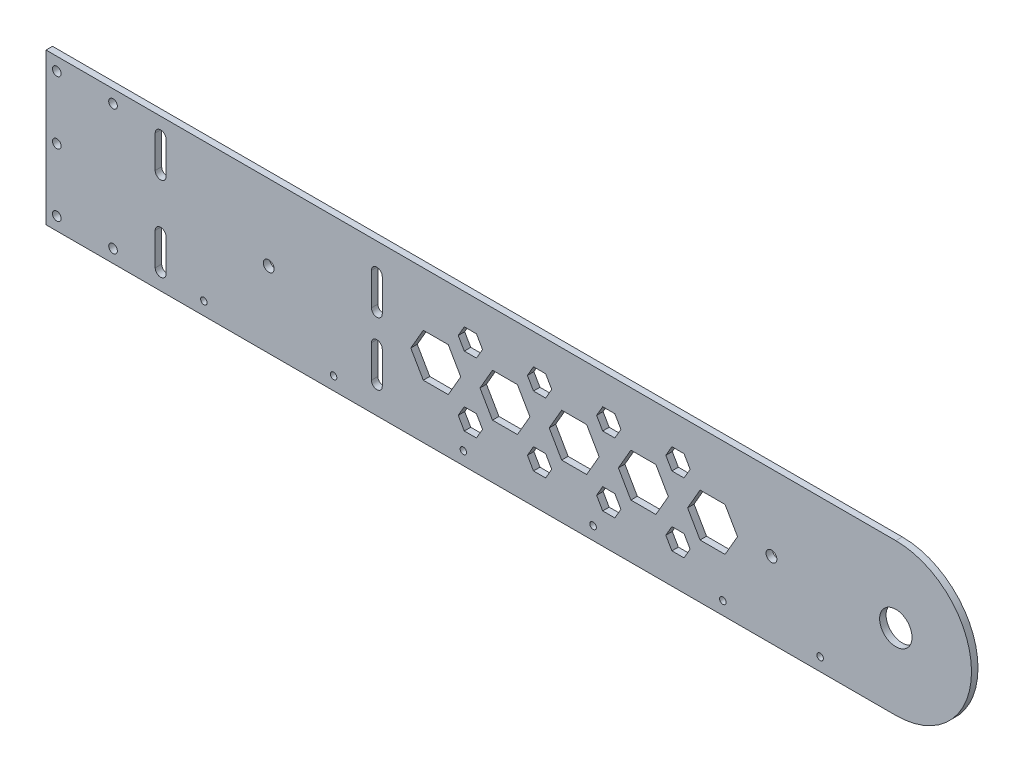
SolidWorks part; units mm, degrees
material "6061 Alloy"
ref_plane "Front Plane" through (0, 0, 0) normal (0, 0, 1) x (1, 0, 0)
ref_plane "Top Plane" through (0, 0, 0) normal (0, 1, 0) x (1, 0, 0)
ref_plane "Right Plane" through (0, 0, 0) normal (1, 0, 0) x (0, 0, -1)
sketch "Sketch1" plane through (0, 0, 0) normal (0, 0, 1) x (1, 0, 0)
  line L0 (0, 0) -> (45.8221, 0) construction
  line L1 (0, 35) -> (393, 35) construction
  line L2 (0, 35) -> (0, -35)
  line L3 (0, -35) -> (393, -35) construction
  line L5 (0, 35) -> (393, 35)
  line L6 (393, -35) -> (0, -35)
  circle A0 centre (5, 29) radius 2
  circle A2 centre (5, -29) radius 2
  circle A4 centre (393, 0) radius 7.5
  circle A7 centre (103, 0) radius 2.5
  circle A8 centre (31, 29) radius 2
  circle A9 centre (31, -29) radius 2
  circle A10 centre (5, 0) radius 2
  arc A11 (393, 35) -> (393, -35) centre (393, 0) cw
  point P0 (0, 0)
  point P8 (153, 0)
  point P14 (53, 0)
  point P16 (0, 0)
  dimension "D2" = 4
  dimension "D5" = 393
  dimension "D10" = 15
  dimension "D6" = 50
  dimension "D7" = 50
  dimension "D14" = 5
  dimension "D8" = 4
  dimension "D11" = 4
  dimension "D15" = 4
  dimension "D1" = 70
  dimension "D3" = 5
  dimension "D4" = 6
  dimension "D9" = 0
  dimension "D12" = 290
  dimension "D13" = 26
extrude "Boss-Extrude1" add sketch "Sketch1" along normal blind 3
sketch "Sketch3" plane through (0, 0, 3) normal (0, 0, 1) x (1, 0, 0)
  line L0 (53, 110.2799) -> (53, -110.2799)
  line L1 (153, 124.2968) -> (153, -124.2968)
  circle A0 centre (103, 0) radius 2.5 construction
  point P3 (53, 0)
  point P6 (153, 0)
  dimension "D1" = 50
  dimension "D2" = 50
split line "Split Line1" [suppressed]
sketch "Sketch4" plane through (0, 0, 3) normal (0, 0, 1) x (1, 0, 0)
  line L0 (53, 27) -> (53, 12) construction
  line L1 (55.5, 27) -> (55.5, 12)
  line L2 (50.5, 27) -> (50.5, 12)
  line L3 (153, 22) -> (153, 7) construction
  line L4 (155.5, 22) -> (155.5, 7)
  line L5 (150.5, 22) -> (150.5, 7)
  line L6 (53, 0) -> (153, 0) construction
  line L7 (153, -22) -> (153, -7) construction
  line L8 (155.5, -22) -> (155.5, -7)
  line L9 (150.5, -22) -> (150.5, -7)
  line L10 (53, -27) -> (53, -12) construction
  line L11 (55.5, -27) -> (55.5, -12)
  line L12 (50.5, -27) -> (50.5, -12)
  arc A0 (55.5, 27) -> (50.5, 27) centre (53, 27) ccw
  arc A1 (50.5, 12) -> (55.5, 12) centre (53, 12) ccw
  arc A2 (155.5, 22) -> (150.5, 22) centre (153, 22) ccw
  arc A3 (150.5, 7) -> (155.5, 7) centre (153, 7) ccw
  circle A4 centre (103, 0) radius 2.5 construction
  arc A5 (155.5, -22) -> (150.5, -22) centre (153, -22) cw
  arc A6 (150.5, -7) -> (155.5, -7) centre (153, -7) cw
  arc A7 (55.5, -27) -> (50.5, -27) centre (53, -27) cw
  arc A8 (50.5, -12) -> (55.5, -12) centre (53, -12) cw
  point P2 (53, 19.5)
  point P8 (153, 14.5)
  point P23 (153, -14.5)
  point P30 (53, -19.5)
  dimension "D1" = 2.5
  dimension "D2" = 2.5
  dimension "D4" = 50
  dimension "D3" = 50
  dimension "D5" = 22
  dimension "D6" = 12
  dimension "D7" = 27
  dimension "D8" = 7
extrude "Cut-Extrude1" cut sketch "Sketch4" against normal through all both and the other way through all
sketch "Sketch5" plane through (0, 0, 3) normal (0, 0, 1) x (1, 0, 0)
  line L0 (284.5811, 0) -> (386.4189, 0) construction
  circle A2 centre (335.5, 0) radius 2.5
  circle A3 centre (103, 0) radius 2.5 construction
  dimension "D1" = 5
  dimension "D2" = 232.5
extrude "Cut-Extrude2" cut sketch "Sketch5" against normal through all both and the other way through all
sketch "Sketch6" plane through (0, 0, 3) normal (0, 0, 1) x (1, 0, 0)
  circle A4 centre (421, 0) radius 1.5
  circle A5 centre (393, -28) radius 1.5
  circle A6 centre (393, 28) radius 1.5
  circle A7 centre (393, 0) radius 7.5 construction
  circle A8 centre (365, 0) radius 1.5
  point P13 (393, 0)
  dimension "D1" = 3
  dimension "D2" = 0
  dimension "D3" = 28
extrude "Cut-Extrude3" [suppressed] cut sketch "Sketch6" against normal through all both and the other way through all
sketch "Sketch7" plane through (0, 0, 3) normal (0, 0, 1) x (1, 0, 0)
  line L1 (73, -29) -> (133, -29) construction
  line L2 (0, -35) -> (393, -35) construction
  circle A0 centre (73, -29) radius 1.5
  circle A2 centre (133, -29) radius 1.5
  circle A3 centre (193, -29) radius 1.5
  circle A4 centre (253, -29) radius 1.5
  circle A5 centre (313, -29) radius 1.5
  circle A12 centre (358, -29) radius 1.5
  circle A13 centre (103, 0) radius 2.5 construction
  dimension "D1" = 3
  dimension "D6" = 3
  dimension "D3" = 30
  dimension "D2" = 6
  dimension "D5" = 60
  dimension "D7" = 45
  dimension "D4" = 5
extrude "Cut-Extrude4" cut sketch "Sketch7" against normal blind 3
sketch "Sketch9" plane through (0, 0, 3) normal (0, 0, 1) x (1, 0, 0)
  line L0 (164.5554, 0) -> (302.378, 0) construction
  line L1 (223.795, 0) -> (218.0215, 10)
  line L2 (191.795, 0) -> (186.0215, 10)
  line L3 (186.0215, 10) -> (174.4745, 10)
  line L4 (174.4745, 10) -> (168.701, 0)
  line L5 (168.701, 0) -> (174.4745, -10)
  line L6 (174.4745, -10) -> (186.0215, -10)
  line L7 (186.0215, -10) -> (191.795, 0)
  line L8 (218.0215, 10) -> (206.4745, 10)
  line L9 (206.4745, 10) -> (200.701, 0)
  line L10 (200.701, 0) -> (206.4745, -10)
  line L11 (206.4745, -10) -> (218.0215, -10)
  line L12 (218.0215, -10) -> (223.795, 0)
  line L13 (255.795, 0) -> (250.0215, 10)
  line L14 (250.0215, 10) -> (238.4745, 10)
  line L15 (238.4745, 10) -> (232.701, 0)
  line L16 (232.701, 0) -> (238.4745, -10)
  line L17 (238.4745, -10) -> (250.0215, -10)
  line L18 (250.0215, -10) -> (255.795, 0)
  line L19 (287.795, 0) -> (282.0215, 10)
  line L20 (282.0215, 10) -> (270.4745, 10)
  line L21 (270.4745, 10) -> (264.701, 0)
  line L22 (264.701, 0) -> (270.4745, -10)
  line L23 (270.4745, -10) -> (282.0215, -10)
  line L24 (282.0215, -10) -> (287.795, 0)
  line L25 (191.795, 0) -> (223.795, 0) construction
  line L26 (233.8658, 16) -> (231.0569, 20.8651)
  line L27 (201.8658, 16) -> (199.0569, 20.8651)
  line L28 (199.0569, 20.8651) -> (193.4391, 20.8651)
  line L29 (193.4391, 20.8651) -> (190.6302, 16)
  line L30 (190.6302, 16) -> (193.4391, 11.1349)
  line L31 (193.4391, 11.1349) -> (199.0569, 11.1349)
  line L32 (199.0569, 11.1349) -> (201.8658, 16)
  line L33 (231.0569, 20.8651) -> (225.4391, 20.8651)
  line L34 (225.4391, 20.8651) -> (222.6302, 16)
  line L35 (222.6302, 16) -> (225.4391, 11.1349)
  line L36 (225.4391, 11.1349) -> (231.0569, 11.1349)
  line L37 (231.0569, 11.1349) -> (233.8658, 16)
  line L38 (265.8658, 16) -> (263.0569, 20.8651)
  line L39 (263.0569, 20.8651) -> (257.4391, 20.8651)
  line L40 (257.4391, 20.8651) -> (254.6302, 16)
  line L41 (254.6302, 16) -> (257.4391, 11.1349)
  line L42 (257.4391, 11.1349) -> (263.0569, 11.1349)
  line L43 (263.0569, 11.1349) -> (265.8658, 16)
  line L44 (201.8658, 16) -> (233.8658, 16) construction
  line L63 (319.795, 0) -> (314.0215, 10)
  line L64 (314.0215, 10) -> (302.4745, 10)
  line L65 (302.4745, 10) -> (296.701, 0)
  line L66 (296.701, 0) -> (302.4745, -10)
  line L67 (302.4745, -10) -> (314.0215, -10)
  line L68 (314.0215, -10) -> (319.795, 0)
  line L69 (297.8658, 16) -> (295.0569, 20.8651)
  line L70 (295.0569, 20.8651) -> (289.4391, 20.8651)
  line L71 (289.4391, 20.8651) -> (286.6302, 16)
  line L72 (286.6302, 16) -> (289.4391, 11.1349)
  line L73 (289.4391, 11.1349) -> (295.0569, 11.1349)
  line L74 (295.0569, 11.1349) -> (297.8658, 16)
  line L75 (295.0569, -11.1349) -> (297.8658, -16)
  line L76 (289.4391, -11.1349) -> (295.0569, -11.1349)
  line L77 (286.6302, -16) -> (289.4391, -11.1349)
  line L78 (289.4391, -20.8651) -> (286.6302, -16)
  line L79 (295.0569, -20.8651) -> (289.4391, -20.8651)
  line L80 (297.8658, -16) -> (295.0569, -20.8651)
  line L81 (263.0569, -11.1349) -> (265.8658, -16)
  line L82 (257.4391, -11.1349) -> (263.0569, -11.1349)
  line L83 (254.6302, -16) -> (257.4391, -11.1349)
  line L84 (257.4391, -20.8651) -> (254.6302, -16)
  line L85 (263.0569, -20.8651) -> (257.4391, -20.8651)
  line L86 (265.8658, -16) -> (263.0569, -20.8651)
  line L87 (231.0569, -11.1349) -> (233.8658, -16)
  line L88 (225.4391, -11.1349) -> (231.0569, -11.1349)
  line L89 (222.6302, -16) -> (225.4391, -11.1349)
  line L90 (225.4391, -20.8651) -> (222.6302, -16)
  line L91 (231.0569, -20.8651) -> (225.4391, -20.8651)
  line L92 (233.8658, -16) -> (231.0569, -20.8651)
  line L93 (199.0569, -11.1349) -> (201.8658, -16)
  line L94 (193.4391, -11.1349) -> (199.0569, -11.1349)
  line L95 (190.6302, -16) -> (193.4391, -11.1349)
  line L96 (193.4391, -20.8651) -> (190.6302, -16)
  line L97 (199.0569, -20.8651) -> (193.4391, -20.8651)
  line L98 (201.8658, -16) -> (199.0569, -20.8651)
  circle A0 centre (180.248, 0) radius 10 construction
  circle A1 centre (196.248, 16) radius 4.8651 construction
  dimension "D1" = 5
  dimension "D2" = 32
  dimension "D3" = 20
  dimension "D5" = 32
  dimension "D6" = 16
  dimension "D8" = 16
  dimension "D4" = 4
extrude "Cut-Extrude6" cut sketch "Sketch9" against normal blind 10
